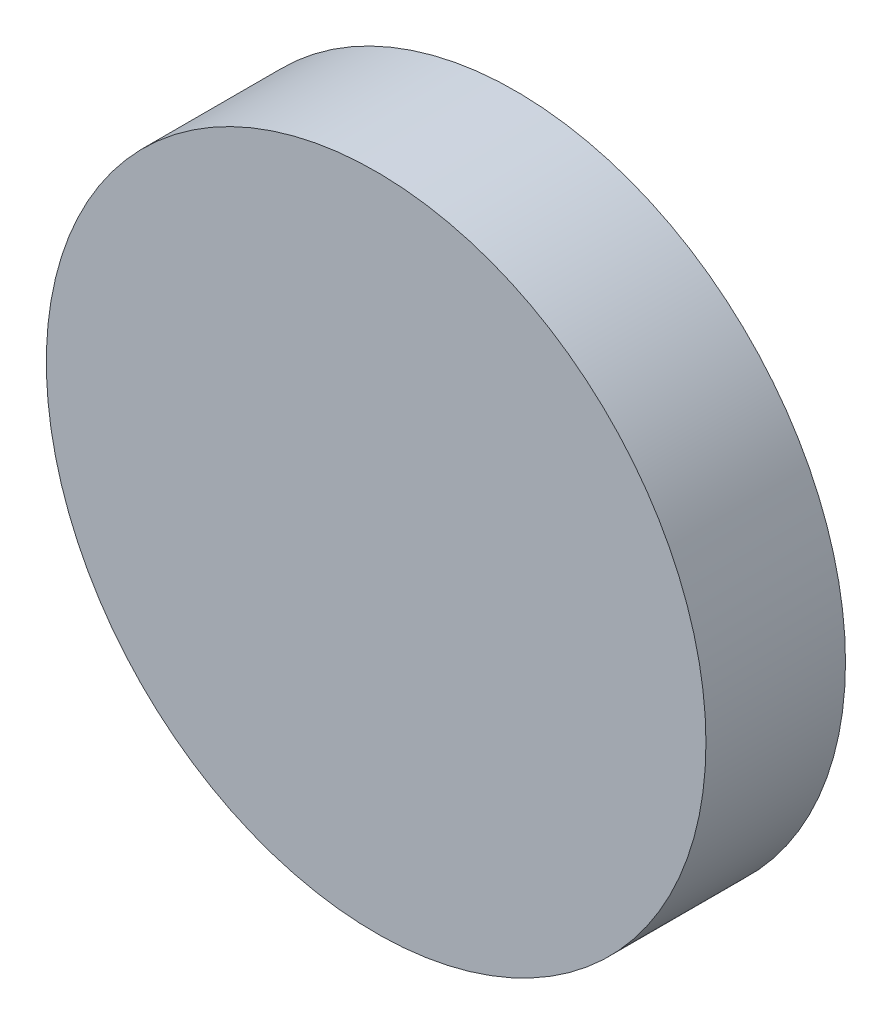
SolidWorks part; units mm, degrees
ref_plane "Front Plane" through (0, 0, 0) normal (0, 0, 1) x (1, 0, 0)
ref_plane "Top Plane" through (0, 0, 0) normal (0, 1, 0) x (1, 0, 0)
ref_plane "Right Plane" through (0, 0, 0) normal (1, 0, 0) x (0, 0, -1)
sketch "Sketch1" plane through (0, 0, 0) normal (0, 0, 1) x (1, 0, 0)
  circle A0 centre (0, 0) radius 78
  dimension "D1" = 156
extrude "Boss-Extrude1" add sketch "Sketch1" along normal blind 33
